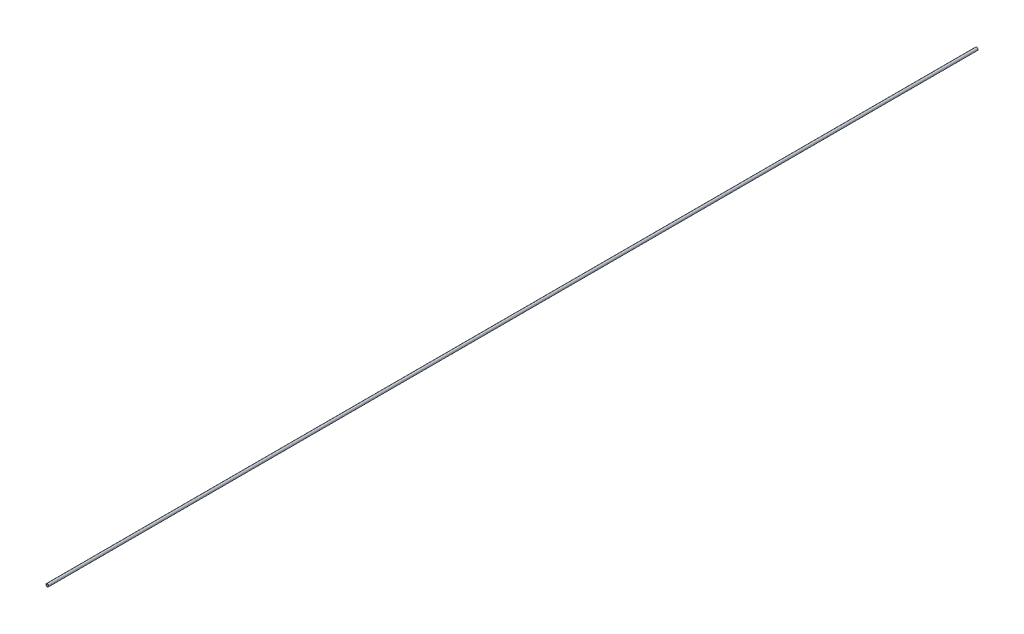
SolidWorks part; units mm, degrees
material "PVC 0.007 Plasticized"
ref_plane "Front Plane" through (0, 0, 0) normal (0, 0, 1) x (1, 0, 0)
ref_plane "Top Plane" through (0, 0, 0) normal (0, 1, 0) x (1, 0, 0)
ref_plane "Right Plane" through (0, 0, 0) normal (1, 0, 0) x (0, 0, -1)
sketch "ProfileS" plane through (0, 0, 0) normal (0, 0, 1) x (1, 0, 0)
  circle A0 centre (0, 0) radius 1.5
  circle A1 centre (0, 0) radius 1
  dimension "OuterDiameter" = 3
  dimension "RefInnerDiameter" = 2
  dimension "OuterWireThickness" = 0.5
extrude "Profile" add sketch "ProfileS" along normal mid plane 1005
